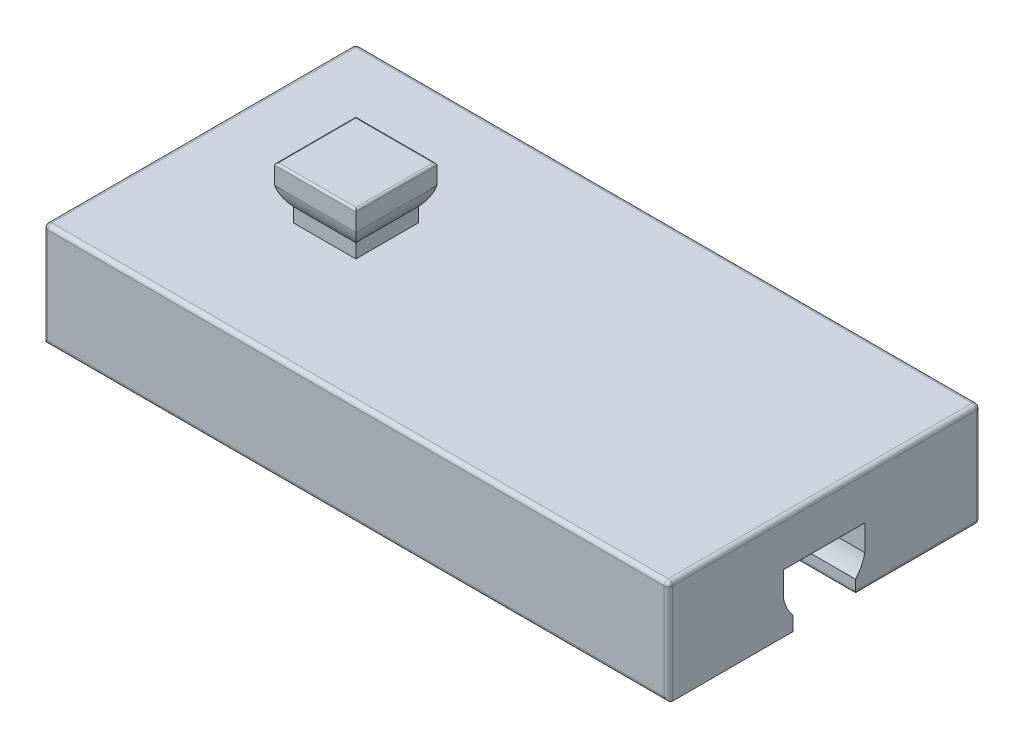
SolidWorks part; units mm, degrees
ref_plane "前视基准面" through (0, 0, 0) normal (0, 0, 1) x (1, 0, 0)
ref_plane "上视基准面" through (0, 0, 0) normal (0, 1, 0) x (1, 0, 0)
ref_plane "右视基准面" through (0, 0, 0) normal (1, 0, 0) x (0, 0, -1)
sketch "草图1" plane through (0, 0, 0) normal (0, 1, 0) x (1, 0, 0)
  line L1 (-15, -7.5) -> (15, -7.5)
  line L2 (-15, -7.5) -> (-15, 7.5)
  line L3 (-15, 7.5) -> (15, 7.5)
  line L4 (15, -7.5) -> (15, 7.5)
extrude "凸台-拉伸1" add sketch "草图1" along normal blind 5
sketch "草图2" plane through (-15, 0, 0) normal (-1, 0, 0) x (0, 0, 1)
  line L0 (-1.5, 0) -> (-1.5, 0.6771)
  line L1 (-7.5, 0) -> (7.5, 0) construction
  line L2 (-1.5, 0) -> (1.5, 0)
  line L3 (1.5, 0) -> (1.5, 0.6771)
  line L4 (-1.95, 2.8) -> (1.95, 2.8)
  line L5 (-1.95, 2.8) -> (-1.95, 1.5556)
  line L6 (1.95, 2.8) -> (1.95, 1.5556)
  arc A0 (-1.95, 1.5556) -> (-1.5, 0.6771) centre (0, 2) ccw
  arc A1 (1.5, 0.6771) -> (1.95, 1.5556) centre (0, 2) ccw
extrude "切除-拉伸1" cut sketch "草图2" against normal up to next
fillet "圆角1" radius 0.2 13 edges at (15, 2.5, -7.5) (-15, 2.5, -7.5) (0, 0, -7.5) (-15, 0, -4.5) (0, 0, -1.5) (-15, 2.5, 7.5) (15, 2.5, 7.5) (0, 0, 7.5) (0, 5, -7.5) (15, 5, 0) (0, 5, 7.5) (-15, 5, 0) (15, 0, -4.5)
sketch "草图3" plane through (0, 5, 0) normal (0, 1, 0) x (-1, 0, 0)
  line L1 (9, 1.5) -> (6, 1.5)
  line L2 (9, 1.5) -> (9, -1.5)
  line L3 (9, -1.5) -> (6, -1.5)
  line L4 (6, 1.5) -> (6, -1.5)
extrude "凸台-拉伸2" add sketch "草图3" along normal blind 1
sketch "草图4" plane through (0, 0, 0) normal (0, 0, 1) x (1, 0, 0)
  line L0 (-9.45, 7.5) -> (-5.55, 7.5)
  line L1 (-9.45, 7.5) -> (-9.45, 6.5556)
  line L2 (-5.55, 7.5) -> (-5.55, 6.5556)
  line L4 (-9, 6) -> (-9, 5) construction
  line L5 (-9, 5.6771) -> (-6, 5.6771)
  arc A0 (-6, 5.6771) -> (-5.55, 6.5556) centre (-7.5, 7) ccw
  arc A1 (-9.45, 6.5556) -> (-9, 5.6771) centre (-7.5, 7) ccw
extrude "凸台-拉伸3" add sketch "草图4" along normal blind 2 and the other way blind 2
sketch "草图5" plane through (-9.45, 0, 0) normal (-1, 0, 0) x (0, 0, 1)
  line L0 (-1.95, 7.5) -> (-1.95, 6.5556)
  line L1 (-2, 5.6771) -> (-1.5, 5.6771)
  line L2 (-2, 5.6771) -> (-2, 7.5)
  line L3 (-2, 7.5) -> (-1.95, 7.5)
  line L4 (2, 5.6771) -> (2, 7.5)
  line L6 (1.95, 7.5) -> (1.95, 6.5556)
  line L7 (1.5, 5.6771) -> (2, 5.6771)
  line L8 (1.95, 7.5) -> (2, 7.5)
  arc A1 (1.5, 5.6771) -> (1.95, 6.5556) centre (0, 7) ccw
  arc A2 (-1.95, 6.5556) -> (-1.5, 5.6771) centre (0, 7) ccw
extrude "切除-拉伸2" cut sketch "草图5" against normal up to next
fillet "圆角2" radius 0.1 4 edges at (-9.45, 7.5, 0) (-7.5, 7.5, -1.95) (-5.55, 7.5, 0) (-7.5, 7.5, 1.95)
